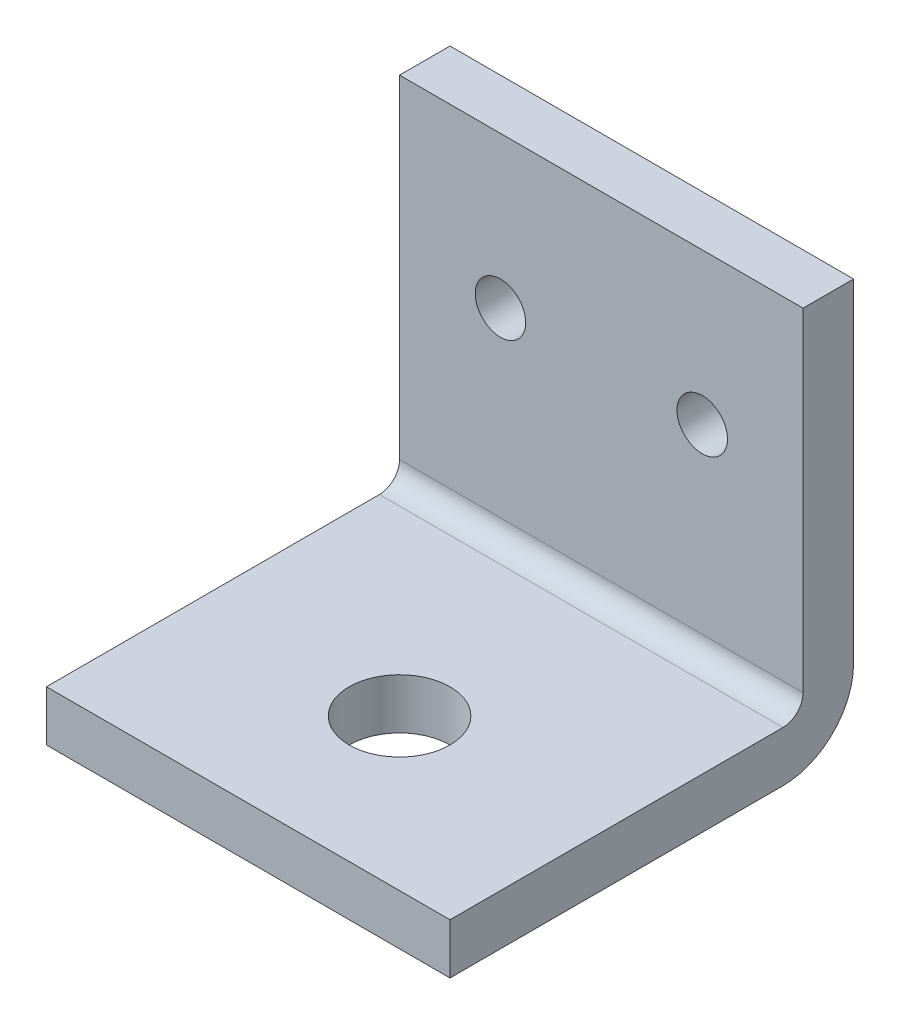
SolidWorks part; units mm, degrees
ref_plane "Front Plane" through (0, 0, 0) normal (1, 0, 0) x (0, 1, 0)
ref_plane "Top Plane" through (0, 0, 0) normal (0, 0, 1) x (0, 1, 0)
ref_plane "Right Plane" through (0, 0, 0) normal (0, 1, 0) x (-1, 0, 0)
sketch "Sketch2" plane through (0, 0, 0) normal (1, 0, 0) x (0, 1, 0)
  line L0 (40, 0) -> (7, 0)
  line L1 (0, 7) -> (0, 40)
  line L2 (0, 40) -> (5, 40)
  line L3 (5, 40) -> (5, 7)
  line L4 (7, 5) -> (40, 5)
  line L5 (40, 5) -> (40, 0)
  arc A0 (0, 7) -> (7, 0) centre (7, 7) ccw
  arc A1 (5, 7) -> (7, 5) centre (7, 7) ccw
  dimension "D4" = 4
  dimension "D2" = 40
  dimension "D3" = 5
  dimension "D5" = 40
extrude "Boss-Extrude1" add sketch "Sketch2" along normal blind 40
sketch "Sketch3" plane through (0, 0, 5) normal (0, 0, 1) x (1, 0, 0)
  line L0 (40, 40) -> (40, 7) construction
  line L1 (40, 40) -> (0, 40) construction
  line L2 (0, 40) -> (0, 7) construction
  line L3 (40, 7) -> (0, 7) construction
  circle A0 centre (10, 25) radius 2.5
  circle A1 centre (30, 25) radius 2.5
  dimension "D3" = 10
  dimension "D4" = 5
  dimension "D5" = 5
  dimension "D1" = 15
  dimension "D2" = 10
  dimension "D6" = 15
extrude "Cut-Extrude2" cut sketch "Sketch3" against normal blind 40 contours A0 | A1
sketch "Sketch4" plane through (0, 0, 0) normal (0, 1, 0) x (-1, 0, 0)
  line L0 (-40, 40) -> (0, 40) construction
  line L1 (-40, 7) -> (-40, 40) construction
  circle A0 centre (-20, 25) radius 5
  dimension "D3" = 10
  dimension "D1" = 15
  dimension "D2" = 20
extrude "Cut-Extrude6" cut sketch "Sketch4" against normal through all both and the other way through all contours A0
